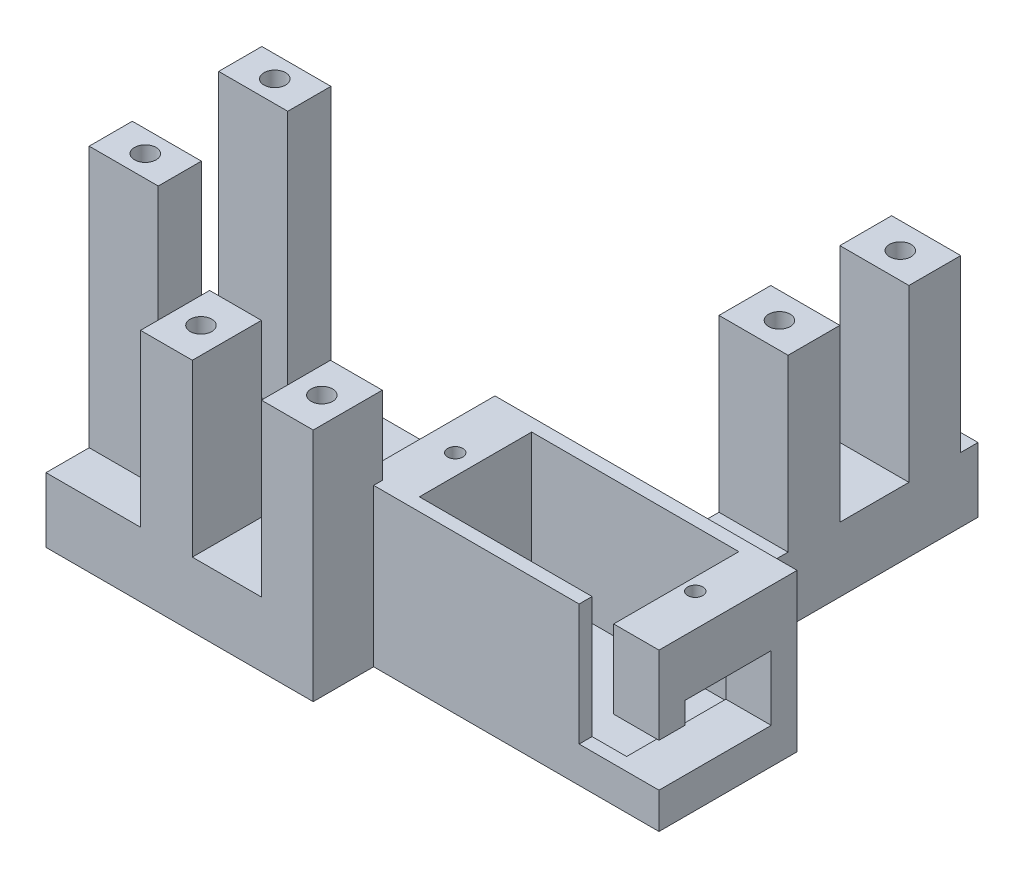
SolidWorks part; units mm, degrees
ref_plane "Front" through (0, 0, 0) normal (0, 0, 1) x (1, 0, 0)
ref_plane "Top" through (0, 0, 0) normal (0, 1, 0) x (1, 0, 0)
ref_plane "Right" through (0, 0, 0) normal (1, 0, 0) x (0, 0, -1)
sketch "Sketch1" plane through (0, 0, 0) normal (0, 1, 0) x (1, 0, 0)
  line L1 (-35, -25) -> (35, -25)
  line L2 (-35, -25) -> (-35, 25)
  line L3 (-35, 25) -> (35, 25)
  line L4 (35, -25) -> (35, 25)
  line L5 (-35, -25) -> (35, 25) construction
  line L6 (-35, 25) -> (35, -25) construction
  point P0 (0, 0)
  dimension "D1" = 50
  dimension "D2" = 70
extrude "Boss-Extrude1" add sketch "Sketch1" along normal blind 7.5
sketch "Sketch2" plane through (0, 7.5, 0) normal (0, 1, 0) x (1, 0, 0)
  line L0 (35, -25) -> (35, 25) construction
  line L1 (35, -25) -> (0, -25)
  line L2 (35, -25) -> (35, -9)
  line L3 (35, -9) -> (0, -9)
  line L4 (0, -25) -> (0, -9)
  line L5 (-35, -25) -> (35, -25) construction
  dimension "D1" = 16
  dimension "D2" = 35
extrude "Boss-Extrude2" add sketch "Sketch2" along normal blind 10.7
sketch "Sketch3" plane through (0, 18.2, 0) normal (0, 1, 0) x (1, 0, 0)
  line L1 (29.75, -10.5) -> (5.75, -10.5)
  line L2 (29.75, -10.5) -> (29.75, -23.5)
  line L3 (29.75, -23.5) -> (5.75, -23.5)
  line L4 (5.75, -10.5) -> (5.75, -23.5)
  line L5 (0, -9) -> (0, -25) construction
  line L6 (35, -9) -> (0, -9) construction
  line L8 (0, -25) -> (35, -25) construction
  dimension "D1" = 24
  dimension "D2" = 1.5
  dimension "D3" = 1.5
  dimension "D4" = 5.75
extrude "Cut-Extrude1" cut sketch "Sketch3" against normal blind 15.7
sketch "Sketch4" plane through (0, 18.2, 0) normal (0, 1, 0) x (1, 0, 0)
  line L2 (29.75, -17) -> (31.2, -17) construction
  line L3 (29.75, -23.5) -> (29.75, -10.5) construction
  line L4 (0, -17) -> (35, -17) construction
  line L5 (0, -9) -> (0, -25) construction
  line L6 (35, -25) -> (35, -9) construction
  circle A0 centre (3.4, -17) radius 0.875
  circle A1 centre (31.2, -17) radius 0.875
  dimension "D2" = 1.75
  dimension "D4" = 1.75
  dimension "D1" = 27.8
  dimension "D3" = 1.45
extrude "Cut-Extrude2" cut sketch "Sketch4" against normal blind 8
sketch "Sketch5" plane through (0, 7.5, 0) normal (0, 1, 0) x (1, 0, 0)
  line L0 (35, -17) -> (21.95, -17) construction
  line L1 (35, -25) -> (35, -9) construction
  line L3 (-35, -25) -> (0, -25) construction
  line L4 (-1.7354, -25) -> (-14.6867, -25)
  line L5 (5.1808, 1.5417) -> (5.1808, 16.5417)
  circle A7 centre (21.95, -17) radius 30 construction
  circle A8 centre (21.95, -17) radius 25 construction
  circle A9 centre (21.95, -17) radius 37.5 construction
  arc A10 (-14.6867, -25) -> (5.1808, 16.5417) centre (21.95, -17) cw
  arc A11 (-1.7354, -25) -> (5.1808, 1.5417) centre (21.95, -17) cw
  circle A12 centre (-1.7354, 3.1758) radius 6
  dimension "D2" = 60
  dimension "D3" = 50
  dimension "D4" = 75
  dimension "D5" = 15
  dimension "D6" = 12
  dimension "D1" = 13.05
sketch "Sketch9" plane through (0, 0, 25) normal (0, 0, 1) x (1, 0, 0)
  line L2 (-35, 7.5) -> (-35, 0)
  line L3 (-35, 0) -> (35, 0)
  line L4 (35, 7.5) -> (35, 0)
  line L11 (-35, 7.5) -> (35, 7.5)
extrude "Boss-Extrude10" add sketch "Sketch9" along normal blind 7
sketch "Sketch10" plane through (0, 7.5, 0) normal (0, 1, 0) x (1, 0, 0)
  line L0 (35, -9) -> (21.95, -9) construction
  line L1 (35, -9) -> (0, -9) construction
  line L2 (21.95, -9) -> (21.95, 3) construction
  line L3 (21.95, 3) -> (21.95, 13) construction
  line L4 (21.95, 13) -> (17.95, 13) construction
  line L5 (17.95, 19) -> (17.95, 7) construction
  line L7 (21.95, 23) -> (13.95, 23)
  line L8 (21.95, 23) -> (21.95, 3)
  line L9 (21.95, 3) -> (13.95, 3)
  line L10 (13.95, 23) -> (13.95, 3)
  line L11 (21.95, 23) -> (13.95, 3) construction
  line L12 (21.95, 3) -> (13.95, 23) construction
  line L13 (-18.05, -32) -> (1.95, -32)
  line L14 (-18.05, -32) -> (-18.05, -24)
  line L15 (-18.05, -24) -> (1.95, -24)
  line L16 (1.95, -32) -> (1.95, -24)
  line L18 (-35, 25) -> (-35, -32) construction
  line L19 (35, -32) -> (-35, -32) construction
  point P10 (17.95, 13)
  dimension "D1" = 13.05
  dimension "D2" = 12
  dimension "D3" = 10
  dimension "D4" = 4
  dimension "D5" = 12
  dimension "D6" = 20
  dimension "D7" = 20
  dimension "D8" = 8
  dimension "D9" = 16.95
extrude "Boss-Extrude11" add sketch "Sketch10" along normal blind 19.75
sketch "Sketch14" plane through (0, 27.25, 0) normal (0, 1, 0) x (1, 0, 0)
  line L3 (1.95, -24) -> (-18.05, -24) construction
  line L4 (13.95, 13) -> (21.95, 13) construction
  line L5 (-12.05, -32) -> (-4.05, -32)
  line L6 (-12.05, -32) -> (-12.05, -24)
  line L7 (-12.05, -24) -> (-4.05, -24)
  line L8 (-4.05, -32) -> (-4.05, -24)
  line L9 (-12.05, -32) -> (-4.05, -24) construction
  line L10 (-12.05, -24) -> (-4.05, -32) construction
  line L11 (13.95, 23) -> (13.95, 3) construction
  line L12 (21.95, 3) -> (21.95, 23) construction
  line L13 (17.95, 3) -> (17.95, 23) construction
  line L14 (13.95, 3) -> (21.95, 3) construction
  line L15 (21.95, 23) -> (13.95, 23) construction
  line L16 (-8.05, -24) -> (-8.05, -32) construction
  line L17 (21.95, 9) -> (13.95, 9)
  line L18 (21.95, 9) -> (21.95, 17)
  line L19 (21.95, 17) -> (13.95, 17)
  line L20 (13.95, 9) -> (13.95, 17)
  line L21 (21.95, 9) -> (13.95, 17) construction
  line L22 (21.95, 17) -> (13.95, 9) construction
  line L23 (-18.05, -28) -> (1.95, -28) construction
  line L24 (-18.05, -24) -> (-18.05, -32) construction
  line L25 (1.95, -32) -> (1.95, -24) construction
  line L26 (-18.05, -32) -> (1.95, -32) construction
  point P2 (-8.05, -28)
  point P20 (17.95, 13)
  point P36 (-8.05, -32)
  dimension "D1" = 8
  dimension "D2" = 8
extrude "Cut-Extrude4" cut sketch "Sketch14" against normal up to surface (19.75 mm away) up to face at (18.475, 7.5, 28.5)
sketch "Sketch15" plane through (0, 27.25, 0) normal (0, 1, 0) x (1, 0, 0)
  line L0 (-15.05, -32) -> (-15.05, -24) construction
  line L1 (-18.05, -32) -> (-12.05, -32) construction
  line L2 (-12.05, -24) -> (-18.05, -24) construction
  line L3 (-1.05, -32) -> (-1.05, -24) construction
  line L4 (-4.05, -32) -> (1.95, -32) construction
  line L5 (1.95, -24) -> (-4.05, -24) construction
  line L6 (21.95, 6) -> (13.95, 6) construction
  line L7 (21.95, 3) -> (21.95, 9) construction
  line L8 (13.95, 9) -> (13.95, 3) construction
  line L9 (21.95, 20) -> (13.95, 20) construction
  line L10 (21.95, 17) -> (21.95, 23) construction
  line L11 (13.95, 23) -> (13.95, 17) construction
  point P6 (-15.05, -28)
  point P13 (-1.05, -28)
  point P26 (17.95, 6)
  point P27 (17.95, 20)
hole_wizard "Tap Drill for M3x0.5 Tap1" positions "3DSketch2" profile "Sketch16" hole size "M3x0.5" standard "ANSI Metric"
sketch3d "3DSketch2"
  point P0 (-15.05, 27.25, 28)
  point P4 (-1.05, 27.25, 28)
  point P7 (17.95, 27.25, -6)
  point P10 (17.95, 27.25, -20)
sketch "Sketch16" plane through (-15.05, 27.25, 28) normal (1, 0, 0) x (0, 0, 1)
  line L0 (0, 0) -> (0, 5.7511)
  line L1 (0, 5.7511) -> (1.25, 5)
  line L2 (1.25, 5) -> (1.25, 0)
  line L5 (1.25, 0) -> (0, 0)
  line L10 (0, 5.7511) -> (-1.25, 5) construction
  line L11 (0, -6.35) -> (0, 107.95) construction
  dimension "Hole Dia." = 2.5
  dimension "Hole Depth" = 5
  dimension "Drill Angle" = 118
sketch "Sketch6" plane through (0, 7.5, 0) normal (0, 1, 0) x (1, 0, 0)
  line L0 (-25, -32) -> (-25, -7) construction
  line L9 (-18.05, -32) -> (-35, -32) construction
  line L10 (-29, -7) -> (-21, -7)
  line L11 (-29, -7) -> (-29, -27)
  line L12 (-29, -27) -> (-21, -27)
  line L13 (-21, -7) -> (-21, -27)
  line L14 (-29, -7) -> (-21, -27) construction
  line L15 (-29, -27) -> (-21, -7) construction
  line L16 (-35, 25) -> (-35, -32) construction
  point P10 (-25, -17)
  dimension "D1" = 10
  dimension "D2" = 15
  dimension "D4" = 20
  dimension "19" = 8
extrude "Boss-Extrude8" add sketch "Sketch6" along normal blind 30.25
sketch "Sketch19" plane through (0, 37.75, 0) normal (0, 1, 0) x (1, 0, 0)
  line L1 (-29, -12) -> (-21, -12)
  line L2 (-29, -12) -> (-29, -22)
  line L3 (-29, -22) -> (-21, -22)
  line L4 (-21, -12) -> (-21, -22)
  line L5 (-29, -12) -> (-21, -22) construction
  line L6 (-29, -22) -> (-21, -12) construction
  line L7 (-21, -27) -> (-21, -7) construction
  line L8 (-25, -7) -> (-25, -27) construction
  line L9 (-21, -7) -> (-29, -7) construction
  line L10 (-29, -27) -> (-21, -27) construction
  line L11 (-21, -17) -> (-29, -17) construction
  line L12 (-21, -27) -> (-21, -7) construction
  line L13 (-29, -7) -> (-29, -27) construction
  point P14 (-25, -17)
  point P20 (-25, -17)
  dimension "D1" = 10
extrude "Cut-Extrude6" cut sketch "Sketch19" against normal up to surface (30.25 mm away) up to face at (-5.6917, 7.5, 16)
sketch "Sketch20" plane through (0, 37.75, 0) normal (0, 1, 0) x (1, 0, 0)
  line L0 (-25, -7) -> (-25, -12) construction
  line L1 (-21, -7) -> (-29, -7) construction
  line L2 (-21, -12) -> (-29, -12) construction
  line L3 (-25, -22) -> (-25, -27) construction
  line L4 (-29, -22) -> (-21, -22) construction
  line L5 (-29, -27) -> (-21, -27) construction
  point P6 (-25, -9.5)
  point P13 (-25, -24.5)
hole_wizard "Tap Drill for M3x0.5 Tap3" positions "3DSketch4" profile "Sketch21" hole size "M3x0.5" standard "ANSI Metric"
sketch3d "3DSketch4"
  point P0 (-25, 37.75, 9.5)
  point P3 (-25, 37.75, 24.5)
sketch "Sketch21" plane through (-25, 37.75, 9.5) normal (1, 0, 0) x (0, 0, 1)
  line L0 (0, 0) -> (0, 5.7511)
  line L1 (0, 5.7511) -> (1.25, 5)
  line L2 (1.25, 5) -> (1.25, 0)
  line L5 (1.25, 0) -> (0, 0)
  line L10 (0, 5.7511) -> (-1.25, 5) construction
  line L11 (0, -6.35) -> (0, 107.95) construction
  dimension "Hole Dia." = 2.5
  dimension "Hole Depth" = 5
  dimension "Drill Angle" = 118
sketch "Sketch22" plane through (0, 7.5, 0) normal (0, 1, 0) x (1, 0, 0)
  line L1 (-35, 25) -> (-35, -32) construction
  line L2 (13.95, -7) -> (13.95, 25)
  line L3 (35, 25) -> (-35, 25) construction
  line L4 (13.95, -7) -> (-29, -7)
  line L8 (35, -9) -> (0, -9) construction
  line L9 (35, 25) -> (21.95, 25)
  line L10 (35, 25) -> (35, -9)
  line L11 (35, -9) -> (21.95, -9)
  line L12 (21.95, 25) -> (21.95, -9)
  line L14 (-29, -22) -> (-29, -27) construction
  line L15 (1.95, -32) -> (35, -32)
  line L16 (1.95, -32) -> (1.95, -25)
  line L17 (1.95, -25) -> (35, -25)
  line L18 (35, -32) -> (35, -25)
  line L19 (-35, -32) -> (-29, -32)
  line L20 (-35, -32) -> (-35, 25)
  line L22 (-29, -32) -> (-29, -7)
  line L23 (-35, 25) -> (13.95, 25)
  line L24 (-21, -7) -> (-29, -7) construction
  line L25 (13.95, 23) -> (13.95, 17) construction
  line L26 (21.95, 17) -> (21.95, 23) construction
extrude "Cut-Extrude7" cut sketch "Sketch22" against normal up to surface (7.5 mm away) up to face at (0, 0, 3.5)
sketch "Sketch24" plane through (-29, 0, 0) normal (-1, 0, 0) x (0, 0, 1)
  line L0 (7, 0) -> (7, 2.5) construction
  line L1 (7, 0) -> (7, 7.5) construction
  line L2 (7, 2.5) -> (9.5, 2.5)
  line L3 (9.5, 2.5) -> (9.5, 6)
  line L4 (9.5, 6) -> (7.5, 6)
  line L5 (7.5, 6) -> (7.5, 5)
  line L6 (7.5, 5) -> (7, 5)
  line L7 (7, 5) -> (7, 2.5)
  line L8 (7, 37.75) -> (7, 0) construction
  dimension "D1" = 2.5
  dimension "D2" = 2.5
  dimension "D3" = 3.5
  dimension "D4" = 0.5
  dimension "D5" = 2.5
extrude "Cut-Extrude8" cut sketch "Sketch24" against normal up to surface (42.95 mm away) up to face at (13.95, 12.8333, -11.6667)
sketch "Sketch25" plane through (29.75, 0, 0) normal (-1, 0, 0) x (0, 0, 1)
  line L0 (17, 18.2) -> (17, 11.65) construction
  line L1 (12, 11.65) -> (22, 11.65)
  line L2 (12, 11.65) -> (12, 4.15)
  line L3 (12, 4.15) -> (22, 4.15)
  line L4 (22, 4.15) -> (22, 11.65)
  line L5 (10.5, 18.2) -> (23.5, 18.2) construction
  point P4 (17, 11.65)
  point P14 (17, 18.2)
  dimension "D1" = 6.55
  dimension "D2" = 10
  dimension "D3" = 7.5
extrude "Cut-Extrude9" cut sketch "Sketch25" against normal up to surface (5.25 mm away) up to face at (35, 9.1, 17)
sketch "Sketch26" plane through (0, 0, 25) normal (0, 0, 1) x (1, 0, 0)
  line L0 (29.75, 18.2) -> (25.75, 18.2)
  line L1 (29.75, 18.2) -> (29.75, 4.15)
  line L2 (29.75, 4.15) -> (25.75, 4.15)
  line L3 (25.75, 18.2) -> (25.75, 4.15)
  line L4 (1.95, 18.2) -> (35, 18.2) construction
  line L5 (35, 4.15) -> (29.75, 4.15) construction
  dimension "D1" = 4
extrude "Cut-Extrude10" cut sketch "Sketch26" against normal up to surface (1.5 mm away) up to face at (17.75, 10.35, 23.5)
sketch "Sketch27" plane through (0, 0, 25) normal (0, 0, 1) x (1, 0, 0)
  line L0 (35, 18.2) -> (35, 0) construction
  line L1 (29.75, 4.15) -> (35, 4.15)
  line L2 (29.75, 4.15) -> (29.75, 9.15)
  line L3 (29.75, 9.15) -> (35, 9.15)
  line L4 (35, 4.15) -> (35, 9.15)
  dimension "D1" = 5
extrude "Cut-Extrude11" cut sketch "Sketch27" against normal up to surface (3 mm away) up to face at (32.375, 7.9, 22)
